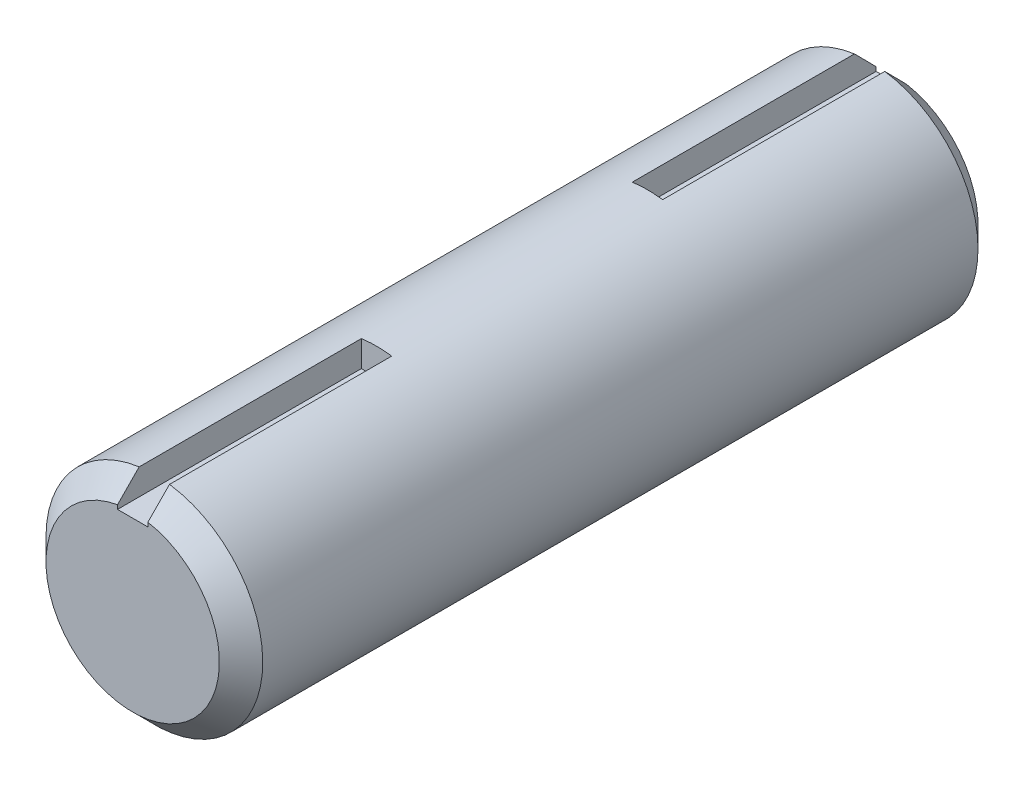
SolidWorks part; units mm, degrees
ref_plane "Front Plane" through (0, 0, 0) normal (0, 0, 1) x (1, 0, 0)
ref_plane "Top Plane" through (0, 0, 0) normal (0, 1, 0) x (1, 0, 0)
ref_plane "Right Plane" through (0, 0, 0) normal (1, 0, 0) x (0, 0, -1)
sketch "Sketch1" plane through (0, 0, 0) normal (0, 0, 1) x (1, 0, 0)
  circle A0 centre (0, 0) radius 12.7
  dimension "D1" = 25.4
extrude "Extrude1" add sketch "Sketch1" against normal blind 88.9
sketch "Sketch2" plane through (0, 0, 0) normal (0, 0, 1) x (1, 0, 0)
  line L0 (0, 0) -> (0, 12.7) construction
  line L1 (-1.778, 12.7) -> (1.778, 12.7)
  line L2 (-1.778, 12.7) -> (-1.778, 11.7027) construction
  line L3 (-1.778, 12.7) -> (-1.778, 9.525)
  line L4 (1.778, 12.7) -> (1.778, 11.7027) construction
  line L5 (1.778, 12.7) -> (1.778, 9.525)
  line L9 (-1.778, 9.525) -> (1.778, 9.525)
  line L10 (-3.9557, 9.525) -> (3.9557, 9.525) construction
  line L11 (-3.9557, 14.8777) -> (3.9557, 14.8777) construction
  line L12 (-3.9557, 14.8777) -> (-3.9557, 9.525) construction
  line L13 (3.9557, 14.8777) -> (3.9557, 9.525) construction
  line L14 (-1.778, 11.7027) -> (1.778, 11.7027) construction
  circle A0 centre (0, 0) radius 12.7 construction
  dimension "D1" = 1.778
  dimension "D2" = 1.778
  dimension "D3" = 3.175
extrude "Extrude2" cut sketch "Sketch2" against normal blind 28.575
chamfer "Chamfer1" distance 2.54 angle 45 1 edges at (0, -12.7, 0)
ref_plane "Plane1" through (0, 0, -44.45) normal (0, 0, 1) x (1, 0, 0)
mirror "Mirror5" about plane through (0, 0, -44.45) normal (0, 0, 1) of "Extrude2"
chamfer "Chamfer2" distance 2.54 angle 45 1 edges at (0, -12.7, -88.9)
